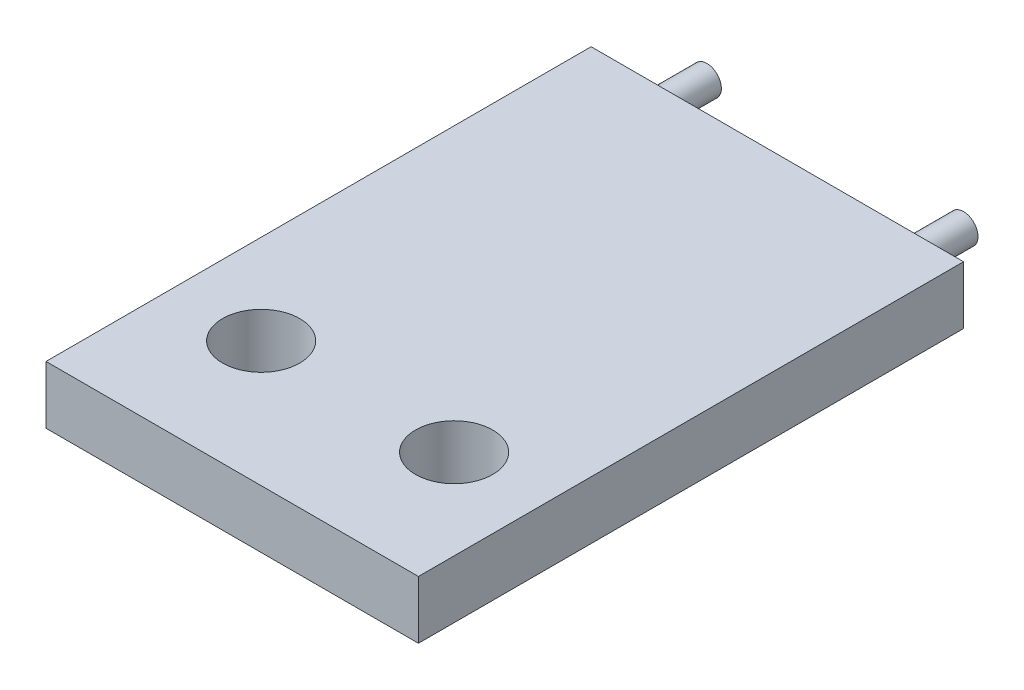
SolidWorks part; units mm, degrees
ref_plane "Front" through (0, 0, 0) normal (0, 0, 1) x (1, 0, 0)
ref_plane "Top" through (0, 0, 0) normal (0, 1, 0) x (1, 0, 0)
ref_plane "Right" through (0, 0, 0) normal (1, 0, 0) x (0, 0, -1)
sketch "Sketch1" plane through (0, 0, 0) normal (0, 1, 0) x (1, 0, 0)
  line L1 (24.511, -50.8) -> (-24.511, -50.8)
  line L2 (24.511, -50.8) -> (24.511, 50.8)
  line L3 (24.511, 50.8) -> (-24.511, 50.8)
  line L4 (-24.511, -50.8) -> (-24.511, 50.8)
  line L5 (24.511, -50.8) -> (-24.511, 50.8) construction
  line L6 (24.511, 50.8) -> (-24.511, -50.8) construction
  point P0 (0, 0)
  dimension "D1" = 49.022
  dimension "D2" = 101.6
extrude "Boss-Extrude1" add sketch "Sketch1" along normal blind 7.62
sketch "Sketch2" plane through (0, 7.62, 0) normal (0, 1, 0) x (1, 0, 0)
  line L0 (0, 50.8) -> (0, -50.8) construction
  line L1 (24.511, 50.8) -> (-24.511, 50.8) construction
  line L2 (-24.511, -50.8) -> (24.511, -50.8) construction
  line L3 (-12.7, 50.8) -> (-12.7, -50.8) construction
  circle A0 centre (-12.7, -34.29) radius 5.08
  circle A1 centre (12.7, -34.29) radius 5.08
  dimension "D2" = 10.16
  dimension "D1" = 12.7
  dimension "D3" = 16.51
extrude "Cut-Extrude1" cut sketch "Sketch2" against normal blind 7.62 contours A1 | A0
sketch "Sketch4" plane through (0, 7.62, 0) normal (0, 1, 0) x (1, 0, 0)
  line L0 (-24.511, -25.4) -> (24.511, -25.4) construction
  line L1 (-24.511, 50.8) -> (-24.511, -50.8) construction
  line L2 (24.511, -50.8) -> (24.511, 50.8) construction
  line L3 (-24.511, -50.8) -> (24.511, -50.8) construction
  line L4 (-24.511, 14.605) -> (24.511, 14.605) construction
  line L5 (0, -50.8) -> (0, 50.8) construction
  line L6 (24.511, 50.8) -> (-24.511, 50.8) construction
  line L7 (-24.511, 20.955) -> (24.511, 20.955) construction
  line L8 (-24.511, 20.955) -> (24.511, 20.955)
  line L9 (24.511, 20.955) -> (24.511, 50.8)
  line L10 (24.511, 50.8) -> (-24.511, 50.8)
  line L11 (-24.511, 50.8) -> (-24.511, 20.955)
  dimension "D1" = 25.4
  dimension "D2" = 40.005
  dimension "D3" = 6.35
extrude "Cut-Extrude2" cut sketch "Sketch4" against normal through all contours L11 L8 L9 L10
sketch "Sketch5" plane through (0, 0, -20.955) normal (0, 0, -1) x (-1, 0, 0)
  line L0 (0, 7.62) -> (0, 0) construction
  line L1 (24.511, 7.62) -> (-24.511, 7.62) construction
  line L2 (-16.891, 7.62) -> (-16.891, 0) construction
  line L3 (24.511, 0) -> (-24.511, 0) construction
  line L4 (-7.62, 7.62) -> (-7.62, 0) construction
  line L5 (7.62, 7.62) -> (7.62, 0) construction
  line L6 (16.891, 7.62) -> (16.891, 0) construction
  line L7 (-24.511, 0) -> (-24.511, 7.62) construction
  line L8 (24.511, 0) -> (24.511, 7.62) construction
  line L9 (-24.511, 3.81) -> (24.511, 3.81) construction
  circle A0 centre (-16.891, 3.81) radius 1.905
  circle A1 centre (-7.62, 3.81) radius 1.905
  circle A2 centre (7.62, 3.81) radius 1.905
  circle A3 centre (16.891, 3.81) radius 1.905
  point P15 (0, 3.81)
  dimension "D5" = 3.81
  dimension "D6" = 3.81
  dimension "D7" = 3.81
  dimension "D8" = 3.81
  dimension "D1" = 7.62
  dimension "D2" = 7.62
  dimension "D3" = 7.62
  dimension "D4" = 7.62
extrude "Cut-Extrude3" cut sketch "Sketch5" against normal blind 17.78
sketch "Sketch6" plane through (0, 0, -3.175) normal (0, 0, -1) x (-1, 0, 0)
  circle A0 centre (-16.891, 3.81) radius 1.905
  circle A1 centre (16.891, 3.81) radius 1.905
extrude "Boss-Extrude3" add sketch "Sketch6" along normal blind 25.4
